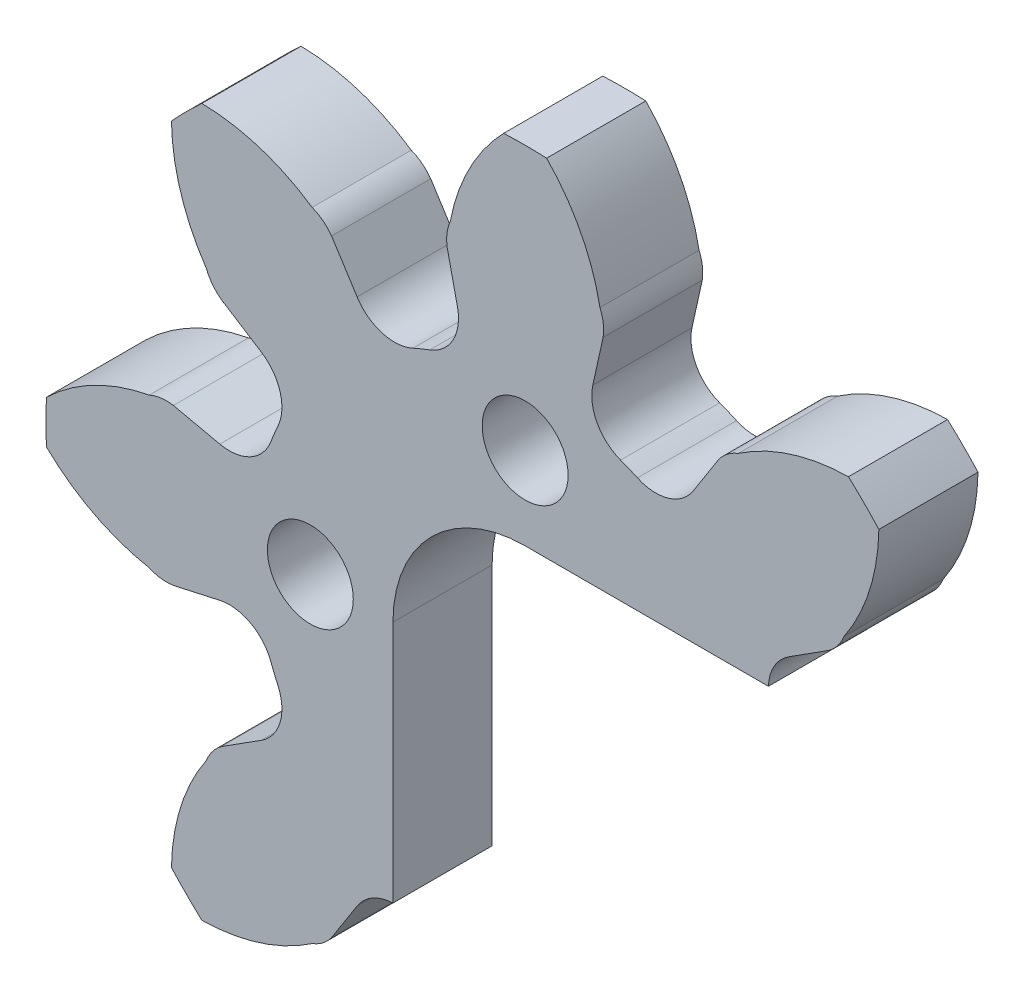
SolidWorks part; units mm, degrees
material "Acrílico (médio-alto impacto)"
ref_plane "Plano frontal" through (0, 0, 0) normal (0, 0, 1) x (1, 0, 0)
ref_plane "Plano superior" through (0, 0, 0) normal (0, 1, 0) x (1, 0, 0)
ref_plane "Plano direito" through (0, 0, 0) normal (1, 0, 0) x (0, 0, -1)
sketch "Posicionamentos" plane through (0, 0, 0) normal (0, 0, 1) x (1, 0, 0)
  circle A0 centre (0, 0) radius 14.5
  circle A1 centre (0, 0) radius 11.6
  circle A2 centre (0, 0) radius 8.2157
  circle A3 centre (0, 0) radius 10.9004
  dimension "De" = 29
  dimension "DP" = 23.2
  dimension "DI" = 16.4314
  dimension "DB" = 21.8009
sketch "Dente" plane through (0, 0, 0) normal (0, 0, 1) x (1, 0, 0)
  line L0 (0, 0) -> (0, 14.5) construction
  line L1 (0, 0) -> (0, 14.5) construction
  line L2 (2.3589, 10.6421) -> (1.7779, 8.021)
  line L3 (2.263, 11.3771) -> (0, 0) construction
  line L4 (-2.3589, 10.6421) -> (-1.7779, 8.021)
  circle A0 centre (0, 0) radius 14.5 construction
  arc A1 (0.6509, 14.4854) -> (2.263, 11.3771) centre (-3.7209, 10.2457) cw
  circle A2 centre (0, 0) radius 11.6 construction
  arc A3 (2.263, 11.3771) -> (2.3589, 10.6421) centre (1.0702, 10.8478) cw
  circle A4 centre (0, 0) radius 10.9004 construction
  circle A5 centre (0, 0) radius 8.2157 construction
  arc A6 (-2.263, 11.3771) -> (-2.3589, 10.6421) centre (-1.0702, 10.8478) ccw
  arc A7 (-0.6509, 14.4854) -> (-2.263, 11.3771) centre (3.7209, 10.2457) ccw
  arc A8 (-1.7779, 8.021) -> (1.7779, 8.021) centre (0, 0) cw
  arc A9 (-0.6509, 14.4854) -> (0.6509, 14.4854) centre (0, 0) cw
  arc A10 (-2.263, 11.3771) -> (2.263, 11.3771) centre (0, 0) cw construction
  dimension "R" = 6.09
  dimension "R1" = 1.305
  dimension "alpha" = 11.25
  dimension "Aposicionador" = 0
  dimension "D1" = 4.5553
sketch "Encaixe" plane through (0, 0, 0) normal (0, 0, 1) x (1, 0, 0)
  line L0 (-4, 0) -> (-4, -13.9374)
  line L4 (0, 4) -> (13.9374, 4)
  arc A4 (0, 4) -> (-4, 0) centre (0, 0) ccw
  circle A5 centre (0, 0) radius 14.5 construction
  arc A6 (-4, -13.9374) -> (13.9374, 4) centre (0, 0) ccw
  dimension "D1" = 8
sketch "Furos" plane through (0, 0, 0) normal (0, 0, 1) x (1, 0, 0)
  line L0 (0, 0) -> (-6.5, 0) construction
  line L1 (0, 0) -> (0, 6.5) construction
  circle A0 centre (0, 0) radius 6.5
  dimension "D1" = 13
extrude "Base" add sketch "Posicionamentos" along normal blind 3 contours A2
hole_wizard "Furo de diâmetro Ø2.6 (2.6)1" positions "Esboço7" profile "Esboço8" hole size "Ø2.6" standard "ISO" end condition through all
sketch "Esboço7" plane through (0, 0, 3) normal (0, 0, 1) x (1, 0, 0)
  point P0 (0, 6.5)
  point P3 (-6.5, 0)
sketch "Esboço8" plane through (0, 6.5, 3) normal (1, 0, 0) x (0, -1, 0)
  line L0 (0, 0) -> (0, 3)
  line L1 (0, 3) -> (1.3, 3)
  line L2 (1.3, 3) -> (1.3, 0)
  line L5 (1.3, 0) -> (0, 0)
  line L11 (0, -6.35) -> (0, 107.95) construction
  dimension "Thru Hole Dia." = 2.6
  dimension "Thru Hole Depth" = 3
extrude "Base Dente" add sketch "Dente" along normal through all
fillet "Raio Dente" radius 1.3424 2 edges at (-1.7779, 8.021, 1.5) (1.7779, 8.021, 1.5)
pattern_circular "PadrãoCircular1" count 8 over 360 about axis through (0, 0, 0) along (0, 0, 1) of "Base Dente", "Raio Dente"
hole_wizard "Furo de diâmetro Ø3.0 (3)1" positions "Esboço4" profile "Esboço5" hole size "Ø3.0" standard "ISO" end condition through all
sketch "Esboço4" plane through (0, 0, 3) normal (0, 0, 1) x (1, 0, 0)
  point P0 (0, 0)
sketch "Esboço5" plane through (0, 0, 3) normal (1, 0, 0) x (0, -1, 0)
  line L0 (0, 0) -> (0, 3)
  line L1 (0, 3) -> (1.5, 3)
  line L2 (1.5, 3) -> (1.5, 0)
  line L5 (1.5, 0) -> (0, 0)
  line L11 (0, -6.35) -> (0, 107.95) construction
  dimension "Thru Hole Dia." = 3
  dimension "Thru Hole Depth" = 3
extrude "Corte-extrusão1" cut sketch "Encaixe" along normal through all
equation "\"Z\"= 8"
equation "\"M\"= 2.9'Módulo"
equation "\"DP\"= \"Z\" * \"M\""
equation "\"P\"= \"M\" * pi'Passo"
equation "\"S\"= \"P\" / 2'Espessura Circular"
equation "\"V\"= \"S\"'Vão"
equation "\"sc\"= 1"
equation "\"de\"= \"M\" * ( \"Z\" + 2 )'Diâmetro Externo"
equation "\"di\"= \"M\" * ( \"Z\" - 2.334 )'Diâmetro Interno"
equation "\"Phi\"= 20'ângulo de pressão"
equation "\"db\"= \"DP\" * cos ( \"Phi\" )'Diâmetro do círculo de base"
equation "\"a\"= \"M\"'Altura da cabeça do dente"
equation "\"b\"= 1.167 * \"M\"'Altura do pé do dente"
equation "\"h\"= \"a\" + \"b\"'Altura do dente"
equation "\"e\"= .167 * \"M\"'Folga no pé do dente"
equation "\"alpha\"= 90 / \"Z\"'ângulo do dente"
equation "\"f\"= \"ValorF@Padrão\""
equation "\"f1\"= \"ValorF1@Padrão\""
equation "\"r\"= \"f\" * \"M\" 'Raio do dente"
equation "\"r1\"= \"f1\" * \"M\"'Rario 1 do dente"
equation "\"De@Posicionamentos\" = \"de\""
equation "\"DP@Posicionamentos\" = \"DP\""
equation "\"DI@Posicionamentos\" = \"di\""
equation "\"DB@Posicionamentos\" = \"db\""
equation "\"R@Dente\" = \"r\""
equation "\"R1@Dente\" = \"r1\""
equation "\"alpha@Dente\" = \"alpha\""
equation "\"D1@PadrãoCircular1\"=\"Z\""
equation "\"rd\"= ( \"db\" - \"di\" ) / 4"
equation "\"D1@Raio Dente\"=\"rd\""
equation "\"Posicionador\"= 1"
equation "\"Aposicionador\"= IIF ( \"Posicionador\" = 0 , 0 , ( \"alpha\" * 2 ) )"
equation "\"D1@Dente\"=\"S\""
